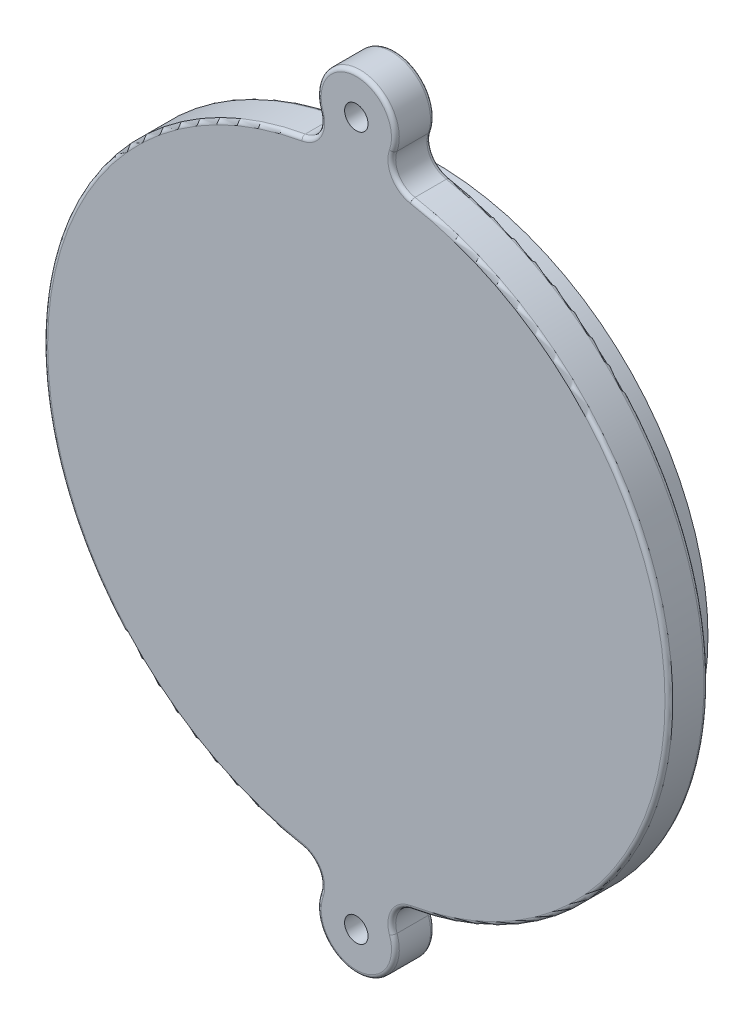
SolidWorks part; units mm, degrees
ref_plane "Plan de face" through (0, 0, 0) normal (0, 0, 1) x (1, 0, 0)
ref_plane "Plan de dessus" through (0, 0, 0) normal (0, 1, 0) x (1, 0, 0)
ref_plane "Plan de droite" through (0, 0, 0) normal (1, 0, 0) x (0, 0, -1)
sketch "Esquisse1" plane through (0, 0, 0) normal (0, 0, 1) x (1, 0, 0)
  line L0 (0, 71.7938) -> (0, -57.9267) construction
  line L1 (-76.7118, 0) -> (114.3111, 0) construction
  arc A0 (-7.0163, 39.3798) -> (-7.0163, -39.3798) centre (0, 0) ccw
  arc A1 (4.714, 43.3333) -> (-4.714, 43.3333) centre (0, 45) ccw
  arc A2 (-7.0163, 39.3798) -> (-4.714, 43.3333) centre (-7.5425, 42.3333) ccw
  arc A3 (7.0163, 39.3798) -> (4.714, 43.3333) centre (7.5425, 42.3333) cw
  circle A4 centre (0, 45) radius 1.5
  arc A5 (7.0163, -39.3798) -> (4.714, -43.3333) centre (7.5425, -42.3333) ccw
  arc A6 (4.714, -43.3333) -> (-4.714, -43.3333) centre (0, -45) cw
  arc A7 (-7.0163, -39.3798) -> (-4.714, -43.3333) centre (-7.5425, -42.3333) cw
  circle A8 centre (0, -45) radius 1.5
  arc A9 (7.0163, -39.3798) -> (7.0163, 39.3798) centre (0, 0) ccw
  dimension "D1" = 80
  dimension "D2" = 10
  dimension "D3" = 6
  dimension "D4" = 3
extrude "Boss.-Extru.1" add sketch "Esquisse1" along normal blind 5
sketch "Esquisse2" plane through (0, 0, 0) normal (0, 0, -1) x (-1, 0, 0)
  circle A0 centre (0, 0) radius 35
  circle A1 centre (0, 0) radius 30.015
  dimension "D1" = 70
  dimension "D2" = 60.03
extrude "Boss.-Extru.2" add sketch "Esquisse2" along normal blind 5
fillet "Congé1" radius 0.5 16 edges at (4.95, -40.8237, 5) (0, -50, 5) (-4.95, -40.8237, 5) (-40, 0, 5) (-4.95, 40.8237, 5) (0, 50, 5) (4.95, 40.8237, 5) (4.95, -40.8237, 0) (0, -50, 0) (-4.95, -40.8237, 0) (-40, 0, 0) (-4.95, 40.8237, 0) (0, 50, 0) (4.95, 40.8237, 0) (40, 0, 5) (40, 0, 0)
fillet "Congé2" radius 1 1 edges at (35, 0, 0)
sketch3d "Esquisse3D1"
  line L0 (0, 0, 0) -> (0, 0, -37.7841) construction
